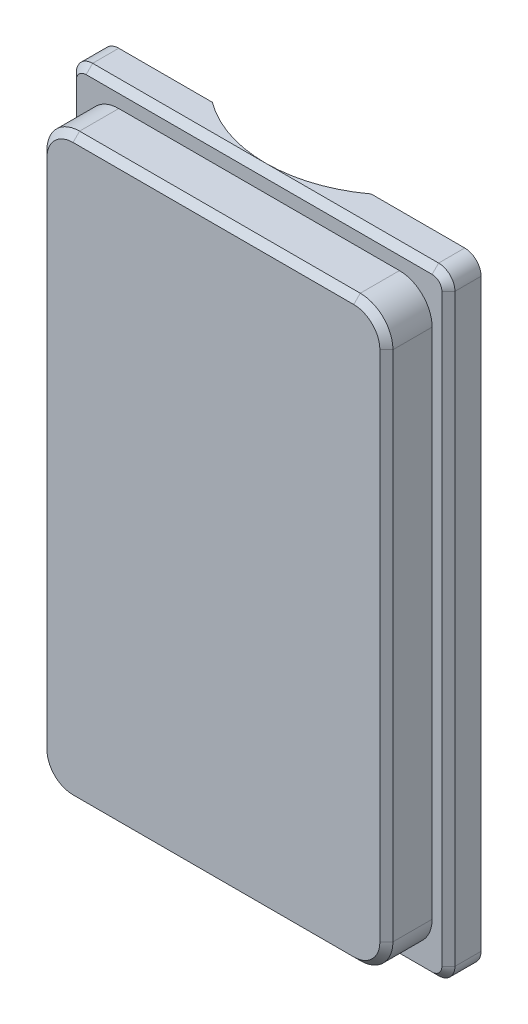
SolidWorks part; units mm, degrees
ref_plane "Front" through (0, 0, 0) normal (0, 0, 1) x (1, 0, 0)
ref_plane "Top" through (0, 0, 0) normal (0, 1, 0) x (1, 0, 0)
ref_plane "Right" through (0, 0, 0) normal (1, 0, 0) x (0, 0, -1)
sketch "草图1" plane through (0, 0, 0) normal (0, 0, 1) x (-1, 0, 0)
  line L0 (-5.8, 61.063) -> (-5.8, 78.973)
  line L1 (0, 92.189) -> (0, 0) construction
  line L2 (-5.3, 79.473) -> (0, 79.473)
  line L3 (0, 79.473) -> (0, 60.563)
  line L4 (-5.3, 60.563) -> (0, 60.563)
  line L20 (-5.9, 61.063) -> (-5.9, 78.973) construction
  line L21 (-5.3, 79.573) -> (-5.3, 91.489) construction
  line L22 (-4.6, 92.189) -> (0, 92.189) construction
  line L23 (0, 92.189) -> (0, 103.1) construction
  line L24 (0, 103.1) -> (-4.1473, 103.1) construction
  line L25 (-5.792, 98.9113) -> (-7.3, 86.073) construction
  line L26 (-7.3, 86.073) -> (-7.3, 0) construction
  line L27 (-7.3, 0) -> (-4.745, 0) construction
  line L28 (-4.745, 0) -> (-4.745, 2.0152) construction
  line L29 (-5.3, 2.7) -> (-5.3, 60.463) construction
  arc A0 (-5.3, 79.473) -> (-5.8, 78.973) centre (-5.3, 78.973) ccw
  arc A1 (-5.8, 61.063) -> (-5.3, 60.563) centre (-5.3, 61.063) ccw
  arc A8 (-5.3, 79.573) -> (-5.9, 78.973) centre (-5.3, 78.973) ccw construction
  arc A9 (-4.6, 92.189) -> (-5.3, 91.489) centre (-4.6, 91.489) ccw construction
  arc A10 (-5.3, 2.7) -> (-4.745, 2.0152) centre (-4.6, 2.7) ccw construction
  arc A11 (-5.9, 61.063) -> (-5.3, 60.463) centre (-5.3, 61.063) ccw construction
  spline S2 degree 3 poles (-4.1473, 103.1) (-4.5698, 102.4681) (-4.9219, 101.7998) (-5.4804, 100.3878) (-5.6807, 99.6588) (-5.792, 98.9113) knots 0 0 0 0 0.5 0.5 1 1 1 1 construction
  dimension "D1" = 0.1
extrude "凸台-拉伸1" add sketch "草图1" along normal blind 1
sketch "草图2" plane through (0, 0, 0) normal (0, 0, 1) x (-1, 0, 0)
  line L20 (-5.9, 61.063) -> (-5.9, 78.973)
  line L21 (-5.3, 79.573) -> (-5.3, 91.489)
  line L22 (-4.6, 92.189) -> (0, 92.189)
  line L23 (0, 92.189) -> (0, 103.1)
  line L24 (0, 103.1) -> (-4.1473, 103.1)
  line L25 (-5.792, 98.9113) -> (-7.3, 86.073)
  line L26 (-7.3, 86.073) -> (-7.3, 0)
  line L27 (-7.3, 0) -> (-4.745, 0)
  line L28 (-4.745, 0) -> (-4.745, 2.0152)
  line L29 (-5.3, 2.7) -> (-5.3, 60.463)
  arc A8 (-5.3, 79.573) -> (-5.9, 78.973) centre (-5.3, 78.973) ccw
  arc A9 (-4.6, 92.189) -> (-5.3, 91.489) centre (-4.6, 91.489) ccw
  arc A10 (-5.3, 2.7) -> (-4.745, 2.0152) centre (-4.6, 2.7) ccw
  arc A11 (-5.9, 61.063) -> (-5.3, 60.463) centre (-5.3, 61.063) ccw
  spline S2 degree 3 poles (-4.1473, 103.1) (-4.5698, 102.4681) (-4.9219, 101.7998) (-5.4804, 100.3878) (-5.6807, 99.6588) (-5.792, 98.9113) knots 0 0 0 0 0.5 0.5 1 1 1 1
sketch "草图3" plane through (0, 0, 1) normal (0, 0, 1) x (1, 0, 0)
  line L3 (0, -60.563) -> (0, -79.473) construction
  line L4 (-5.3, -61.163) -> (5.3, -61.163) construction
  line L5 (-5.3, -61.163) -> (-5.3, -78.873) construction
  line L6 (-5.3, -78.873) -> (5.3, -78.873) construction
  line L7 (5.3, -61.163) -> (5.3, -78.873) construction
  line L8 (-5.3, -61.163) -> (5.3, -78.873) construction
  line L9 (-5.3, -78.873) -> (5.3, -61.163) construction
  line L10 (5.9, -61.063) -> (5.9, -78.973) construction
  line L11 (5.3, -60.563) -> (0, -60.563) construction
  line L12 (0, -61.163) -> (0, -78.873)
  line L13 (0, -61.163) -> (5.3, -61.163)
  line L14 (5.3, -61.163) -> (5.3, -78.873)
  line L15 (5.3, -78.873) -> (0, -78.873)
  point P4 (2.65, -60.563)
  point P6 (0, -70.018)
  dimension "D1" = 0.6
  dimension "D2" = 0.6
extrude "凸台-拉伸2" add sketch "草图3" along normal blind 1.4
fillet "圆角1" radius 1 2 edges at (5.3, -61.163, 1.7) (5.3, -78.873, 1.7)
mirror "镜向1" about plane through (0, -79.473, 1) normal (1, 0, 0) of bodies 102
chamfer "倒角1" distance 0.2 angle 45 16 edges at (-5.8, -70.018, 1) (-5.6536, -79.3266, 1) (-5.6536, -60.7094, 1) (0, -79.473, 1) (0, -60.563, 1) (5.6536, -79.3266, 1) (5.6536, -60.7094, 1) (5.8, -70.018, 1) (-5.3, -70.018, 2.4) (-5.0071, -78.5801, 2.4) (-5.0071, -61.4559, 2.4) (0, -78.873, 2.4) (0, -61.163, 2.4) (5.0071, -78.5801, 2.4) (5.0071, -61.4559, 2.4) (5.3, -70.018, 2.4)
sketch "草图4" plane through (-6.3, -79.273, 0) normal (0, 0, 1) x (1, 0, 0)
  line L0 (5.1226, 18.2297) -> (5.1226, 0.5608) construction
  line L1 (6.3, -0.2) -> (6.3, 18.71) construction
  line L2 (1, -0.2) -> (11.6, -0.2) construction
  line L3 (11.6, 18.71) -> (1, 18.71) construction
  text T1 "OldGerman" font "DS ISO 1" height 2.4
extrude "切除-拉伸1" cut sketch "草图4" along normal blind 0.5
sketch "草图5" plane through (0, -79.473, 0) normal (0, -1, 0) x (1, 0, 0)
  line L0 (0, 0) -> (0, 50000) construction
  line L1 (-5.3, 0) -> (5.3, 0) construction
  line L2 (5.3, 0.8) -> (-5.3, 0.8) construction
  circle A0 centre (0, -3.3) radius 4.1
  circle A1 centre (0, -3.3) radius 2.75 construction
  point P4 (0, 0)
  dimension "D1" = 8.2
extrude "切除-拉伸2" cut sketch "草图5" against normal through all
